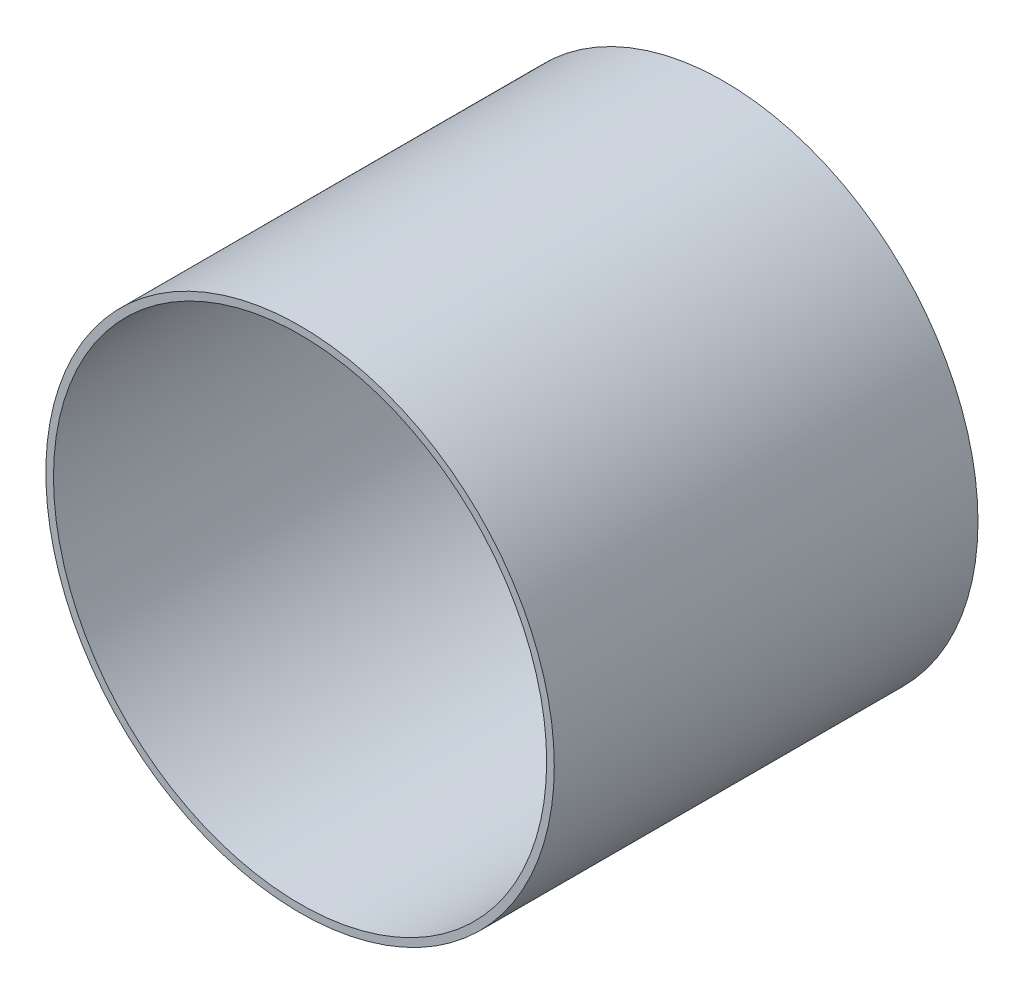
SolidWorks part; units mm, degrees
ref_plane "Front Plane" through (0, 0, 0) normal (0, 0, 1) x (1, 0, 0)
ref_plane "Top Plane" through (0, 0, 0) normal (0, 1, 0) x (1, 0, 0)
ref_plane "Right Plane" through (0, 0, 0) normal (1, 0, 0) x (0, 0, -1)
sketch "Sketch1" plane through (0, 0, 0) normal (0, 0, 1) x (1, 0, 0)
  circle A0 centre (0, 0) radius 14.55
  circle A1 centre (0, 0) radius 15
  dimension "D1" = 30
  dimension "D2" = 29.1
extrude "Boss-Extrude1" add sketch "Sketch1" along normal blind 25
